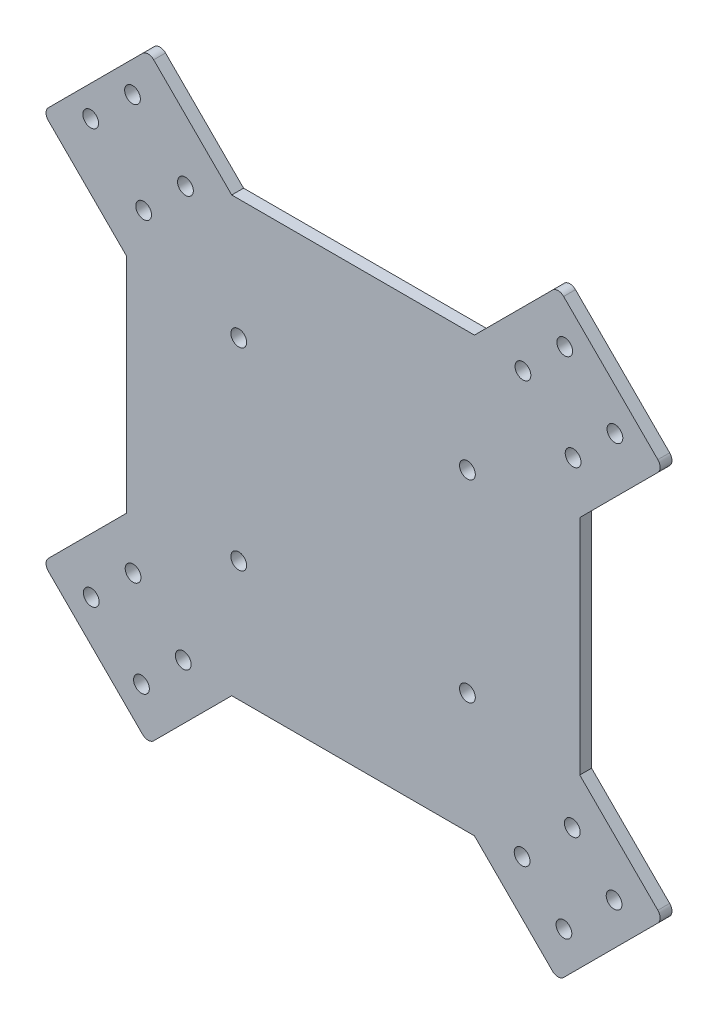
SolidWorks part; units mm, degrees
ref_plane "Front Plane" through (0, 0, 0) normal (0, 0, 1) x (1, 0, 0)
ref_plane "Top Plane" through (0, 0, 0) normal (0, 1, 0) x (1, 0, 0)
ref_plane "Right Plane" through (0, 0, 0) normal (1, 0, 0) x (0, 0, -1)
sketch "Sketch1" plane through (0, 0, 0) normal (0, 0, 1) x (1, 0, 0)
  line L0 (0, 0) -> (0, 47150.9256) construction
  line L1 (0, 0) -> (47150.9256, 0) construction
  line L7 (57.5, -28.28) -> (78.7132, -49.4932)
  line L9 (-30.78, 55) -> (30.78, 55)
  line L10 (-57.5, 28.28) -> (-57.5, -28.28)
  line L11 (-30.78, -55) -> (30.78, -55)
  line L12 (57.5, 28.28) -> (57.5, -28.28)
  line L13 (-57.5, 55) -> (57.5, -55) construction
  line L14 (-57.5, -55) -> (57.5, 55) construction
  line L18 (-29, 24.5) -> (29, 24.5) construction
  line L19 (-29, 24.5) -> (-29, -24.5) construction
  line L20 (-29, -24.5) -> (29, -24.5) construction
  line L21 (29, 24.5) -> (29, -24.5) construction
  line L22 (-29, 24.5) -> (29, -24.5) construction
  line L23 (-29, -24.5) -> (29, 24.5) construction
  line L24 (78.7132, -49.4932) -> (51.9932, -76.2132)
  line L25 (51.9932, -76.2132) -> (30.78, -55)
  line L26 (-57.5, -28.28) -> (-78.7132, -49.4932)
  line L27 (-78.7132, -49.4932) -> (-51.9932, -76.2132)
  line L28 (-51.9932, -76.2132) -> (-30.78, -55)
  line L29 (-51.9932, 76.2132) -> (-30.78, 55)
  line L30 (-78.7132, 49.4932) -> (-51.9932, 76.2132)
  line L31 (-57.5, 28.28) -> (-78.7132, 49.4932)
  line L32 (30.78, 55) -> (51.9932, 76.2132)
  line L33 (51.9932, 76.2132) -> (78.7132, 49.4932)
  line L34 (78.7132, 49.4932) -> (57.5, 28.28)
  line L35 (-28.28, -57.5) -> (-49.4932, -78.7132) [skipped]
  line L36 (-49.4932, -78.7132) -> (-76.2132, -51.9932) [skipped]
  line L37 (-76.2132, -51.9932) -> (-55, -30.78) [skipped]
  line L38 (49.4932, 78.7132) -> (76.2132, 51.9932) [skipped]
  line L39 (76.2132, 51.9932) -> (55, 30.78) [skipped]
  line L40 (28.28, 57.5) -> (49.4932, 78.7132) [skipped]
  circle A4 centre (-29, 24.5) radius 2
  circle A5 centre (-29, -24.5) radius 2
  circle A6 centre (29, 24.5) radius 2
  circle A7 centre (29, -24.5) radius 2
  arc A8 (-41.3866, 65.6066) -> (41.3866, 65.6066) centre (0, 141.0479) ccw
  arc A9 (-68.1066, 38.8866) -> (-68.1066, -38.8866) centre (-134.0876, 0) cw
  arc A10 (68.1066, 38.8866) -> (68.1066, -38.8866) centre (134.0876, 0) ccw
  arc A11 (-41.3866, -65.6066) -> (41.3866, -65.6066) centre (0, -141.0479) cw
  point P5 (0, 0)
  point P43 (0, 0)
  point P61 (0, 0)
  dimension "D3" = 58
  dimension "D4" = 4
  dimension "D7" = 4
  dimension "D8" = 4
  dimension "D9" = 4
  dimension "D1" = 49
  dimension "D5" = 115
  dimension "D6" = 110
  dimension "D10" = 45
  dimension "D11" = 30
  dimension "D12" = 45
  dimension "D14" = 45
  dimension "D15" = 45
  dimension "D16" = 30
  dimension "D17" = 45
  dimension "D18" = 45
  dimension "D19" = 30
  dimension "D20" = 37.7878
  dimension "D13" = 4
extrude "Boss-Extrude1" add sketch "Sketch1" along normal blind 3 contours L34 L33 L32 L9 L29 L30 L31 L10 L26 L27 L28 L11 L25 L24 L7 L12 A7 A6 A5 A4
sketch "Sketch2" plane through (0, 0, 3) normal (0, 0, 1) x (1, 0, 0)
  line L0 (30.78, 55) -> (57.5, 28.28) construction
  line L1 (44.14, 41.64) -> (71.2882, 68.7882) construction
  line L2 (43.0793, 53.3073) -> (53.6859, 63.9139) construction
  line L3 (43.0793, 53.3073) -> (55.8073, 40.5793) construction
  line L4 (55.8073, 40.5793) -> (66.4139, 51.1859) construction
  line L5 (53.6859, 63.9139) -> (66.4139, 51.1859) construction
  line L6 (43.0793, 53.3073) -> (66.4139, 51.1859) construction
  line L7 (55.8073, 40.5793) -> (53.6859, 63.9139) construction
  line L8 (0, 0) -> (-36037.9104, 34659.328) construction
  line L9 (-57.5, -28.28) -> (-30.78, -55) construction
  line L10 (-78.7132, -49.4932) -> (-51.9932, -76.2132) construction
  line L11 (-65.3532, -62.8532) -> (-37.2147, -34.7147) construction
  line L12 (-78.7132, 49.4932) -> (-51.9932, 76.2132) construction
  line L13 (-57.5, 28.28) -> (-30.78, 55) construction
  line L14 (-66.4139, -51.1859) -> (-55.8073, -40.5793) construction
  line L15 (-66.4139, -51.1859) -> (-53.6859, -63.9139) construction
  line L16 (-53.6859, -63.9139) -> (-43.0793, -53.3073) construction
  line L17 (-55.8073, -40.5793) -> (-43.0793, -53.3073) construction
  line L18 (-66.4139, -51.1859) -> (-43.0793, -53.3073) construction
  line L19 (-53.6859, -63.9139) -> (-55.8073, -40.5793) construction
  line L20 (30.78, -55) -> (57.5, -28.28) construction
  line L21 (-41.3866, 65.6066) -> (-68.1066, 38.8866) construction
  line L22 (-66.5553, 53.8624) -> (-55.9487, 64.469) construction
  line L23 (-66.5553, 53.8624) -> (-53.1308, 40.4379) construction
  line L24 (-53.1308, 40.4379) -> (-42.5242, 51.0445) construction
  line L25 (-55.9487, 64.469) -> (-42.5242, 51.0445) construction
  line L26 (-66.5553, 53.8624) -> (-42.5242, 51.0445) construction
  line L27 (-53.1308, 40.4379) -> (-55.9487, 64.469) construction
  line L28 (-51.9932, 76.2132) -> (-30.78, 55) construction
  line L29 (-57.5, 28.28) -> (-78.7132, 49.4932) construction
  line L31 (42.8725, -53.5141) -> (55.6004, -40.7862) construction
  line L32 (42.8725, -53.5141) -> (53.4791, -64.1207) construction
  line L33 (53.4791, -64.1207) -> (66.207, -51.3928) construction
  line L34 (55.6004, -40.7862) -> (66.207, -51.3928) construction
  line L35 (42.8725, -53.5141) -> (66.207, -51.3928) construction
  line L36 (53.4791, -64.1207) -> (55.6004, -40.7862) construction
  line L58 (-57.5, 0) -> (-26.4925, 0) construction
  line L59 (-57.5, 28.28) -> (-57.5, -28.28) construction
  line L60 (0, 0) -> (0, 50000) construction
  circle A0 centre (43.0793, 53.3073) radius 2
  circle A1 centre (53.6859, 63.9139) radius 2
  circle A2 centre (55.8073, 40.5793) radius 2
  circle A3 centre (66.4139, 51.1859) radius 2
  circle A4 centre (-66.4139, -51.1859) radius 2
  circle A5 centre (-55.8073, -40.5793) radius 2
  circle A6 centre (-43.0793, -53.3073) radius 2
  circle A7 centre (-53.6859, -63.9139) radius 2
  circle A8 centre (-55.9487, 64.469) radius 2
  circle A9 centre (-42.5242, 51.0445) radius 2
  circle A10 centre (-53.1308, 40.4379) radius 2
  circle A11 centre (-66.5553, 53.8624) radius 2
  circle A12 centre (55.6004, -40.7862) radius 2
  circle A13 centre (42.8725, -53.5141) radius 2
  circle A14 centre (66.207, -51.3928) radius 2
  circle A15 centre (53.4791, -64.1207) radius 2
  point P4 (54.7466, 52.2466)
  point P18 (-54.7466, -52.2466)
  point P32 (-44.14, -41.64)
  point P38 (-65.3532, 62.8532)
  point P47 (-54.5398, 52.4534)
  point P53 (-52.6697, 53.5593)
  point P63 (54.5398, -52.4534)
  point P120 (0, 0)
  dimension "D8" = 4
  dimension "D9" = 4
  dimension "D10" = 4
  dimension "D11" = 4
  dimension "D12" = 18
  dimension "D19" = 4
  dimension "D20" = 4
  dimension "D21" = 4
  dimension "D22" = 4
  dimension "D29" = 4
  dimension "D30" = 4
  dimension "D31" = 4
  dimension "D32" = 4
  dimension "D40" = 4
  dimension "D41" = 4
  dimension "D42" = 4
  dimension "D43" = 4
  dimension "D1" = 15
  dimension "D2" = 18
  dimension "D3" = 90
  dimension "D4" = 90
  dimension "D5" = 90
  dimension "D6" = 15
  dimension "D7" = 90
  dimension "D13" = 90
  dimension "D14" = 90
  dimension "D15" = 90
  dimension "D16" = 15
  dimension "D17" = 90
  dimension "D18" = 15
  dimension "D23" = 90
  dimension "D24" = 90
  dimension "D25" = 90
  dimension "D26" = 90
  dimension "D27" = 18.9851
  dimension "D28" = 15
  dimension "D33" = 90
  dimension "D34" = 90
  dimension "D35" = 90
  dimension "D36" = 90
  dimension "D37" = 15
  dimension "D38" = 18
  dimension "D39" = 15
  dimension "D54" = 31.0075
extrude "Cut-Extrude1" cut sketch "Sketch2" against normal through all
fillet "Fillet1" radius 2 8 edges at (-51.9932, 76.2132, 1.5) (-78.7132, 49.4932, 1.5) (51.9932, 76.2132, 1.5) (78.7132, 49.4932, 1.5) (78.7132, -49.4932, 1.5) (51.9932, -76.2132, 1.5) (-78.7132, -49.4932, 1.5) (-51.9932, -76.2132, 1.5)
sketch3d "3DSketch1" plane through (0, 0, 0) normal (0, 0, 1) x (1, 0, 0)
  dimension "D1" = 55
